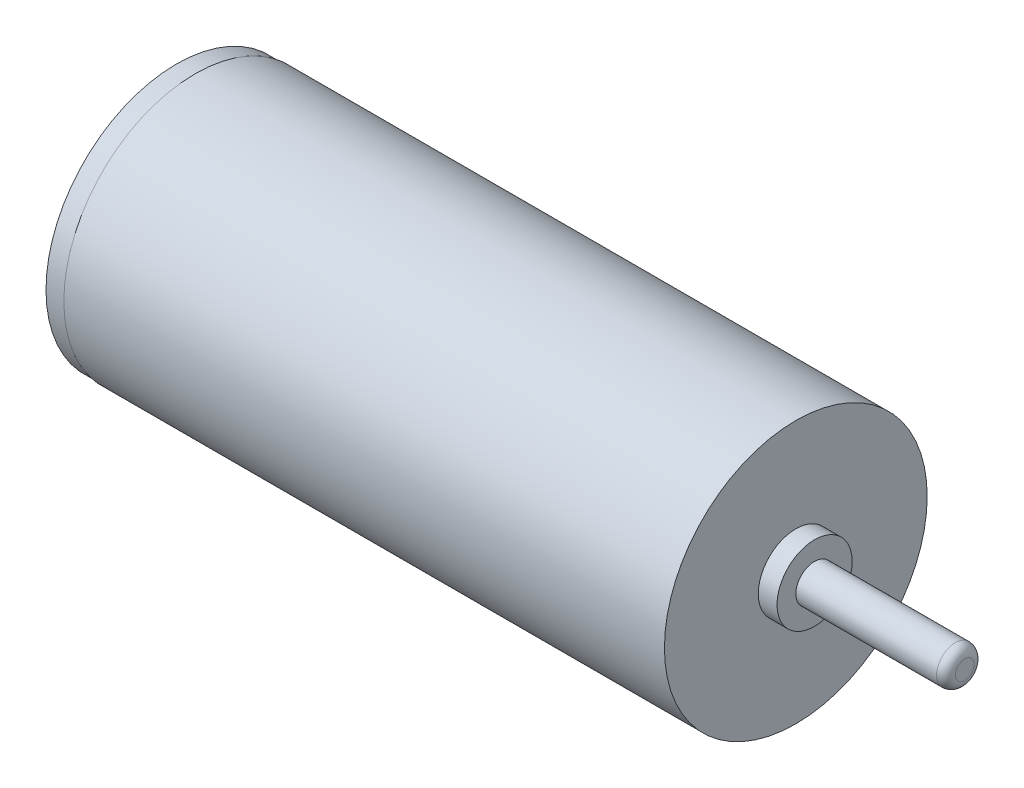
SolidWorks part; units mm, degrees
ref_plane "Front Plane" through (0, 0, 0) normal (0, 0, 1) x (1, 0, 0)
ref_plane "Top Plane" through (0, 0, 0) normal (0, 1, 0) x (1, 0, 0)
ref_plane "Right Plane" through (0, 0, 0) normal (1, 0, 0) x (0, 0, -1)
sketch "Sketch1" plane through (0, 0, 0) normal (1, 0, 0) x (0, 0, -1)
  circle A1 centre (0, 0) radius 3.5
  dimension "D1" = 7
extrude "Boss-Extrude1" add sketch "Sketch1" against normal blind 16
sketch "Sketch2" plane through (0, 0, 0) normal (1, 0, 0) x (0, 0, -1)
  circle A0 centre (0, 0) radius 1
  dimension "D1" = 2
extrude "Boss-Extrude2" add sketch "Sketch2" along normal blind 0.5
sketch "Sketch3" plane through (0.5, 0, 0) normal (1, 0, 0) x (0, 0, -1)
  circle A0 centre (0, 0) radius 0.5
  dimension "D1" = 1
extrude "Boss-Extrude3" add sketch "Sketch3" along normal blind 4
fillet "Fillet1" radius 0.25 1 edges at (4.5, 0, -0.5)
sketch "Sketch7" plane through (-16, 0, 0) normal (-1, 0, 0) x (0, 0, 1)
  circle A0 centre (0, 0) radius 3.475
  dimension "D1" = 6.95
extrude "Boss-Extrude6" add sketch "Sketch7" along normal blind 0.5
sketch "Sketch8" plane through (-16.5, 0, 0) normal (-1, 0, 0) x (0, 0, 1)
  circle A0 centre (0, 0) radius 1
  dimension "D1" = 2
extrude "Boss-Extrude7" add sketch "Sketch8" along normal blind 1
